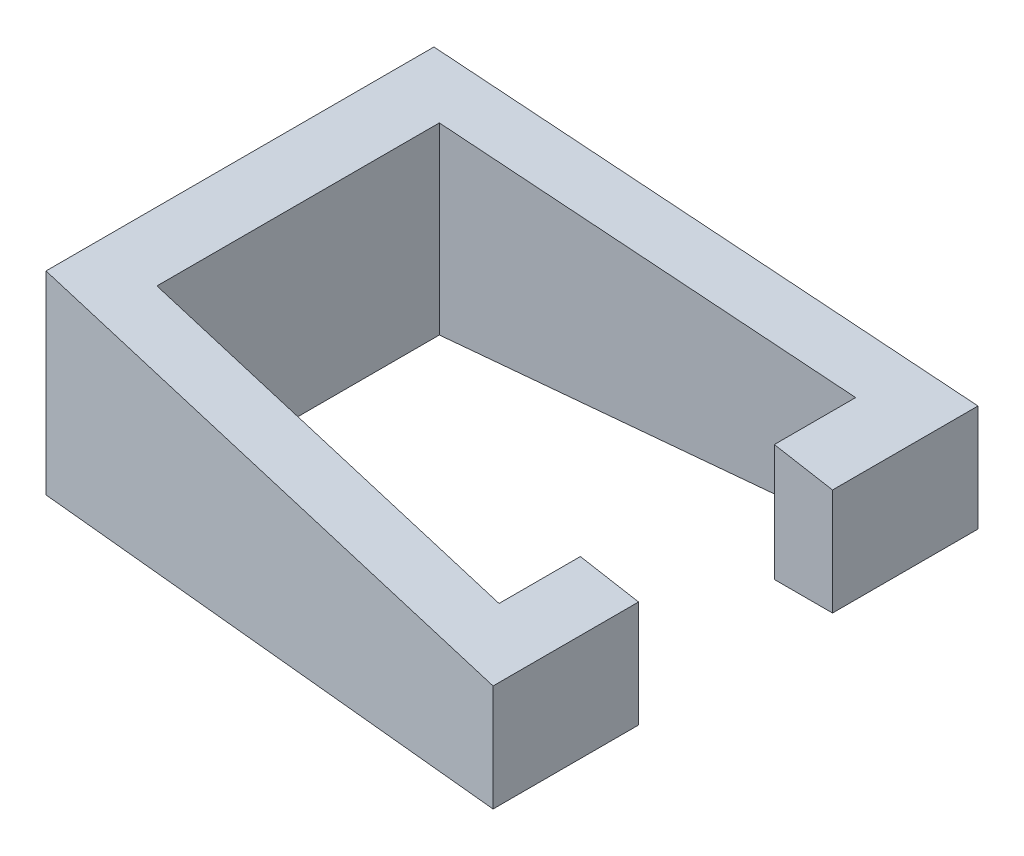
SolidWorks part; units mm, degrees
ref_plane "Front Plane" through (0, 0, 0) normal (0, 0, 1) x (1, 0, 0)
ref_plane "Top Plane" through (0, 0, 0) normal (0, 1, 0) x (1, 0, 0)
ref_plane "Right Plane" through (0, 0, 0) normal (1, 0, 0) x (0, 0, -1)
sketch "Sketch1" plane through (0, 0, 0) normal (0, 1, 0) x (1, 0, 0)
  line L0 (-16.3926, 0) -> (30.937, 0) construction
  line L1 (-10.7677, 0) -> (-10.7677, -10)
  line L2 (-10.7677, -10) -> (14.7803, -12.5)
  line L3 (14.7803, -12.5) -> (14.7803, -5)
  line L4 (-7.7677, 0) -> (-7.7677, -7.2792)
  line L5 (-7.7677, -7.2792) -> (11.7803, -9.1921)
  line L6 (11.7803, -9.1921) -> (11.7803, -5)
  line L8 (14.7803, -5) -> (11.7803, -5)
  line L9 (14.7803, 5) -> (11.7803, 5)
  line L10 (11.7803, 9.1921) -> (11.7803, 5)
  line L11 (-7.7677, 7.2792) -> (11.7803, 9.1921)
  line L12 (-7.7677, 0) -> (-7.7677, 7.2792)
  line L13 (14.7803, 12.5) -> (14.7803, 5)
  line L14 (-10.7677, 10) -> (14.7803, 12.5)
  line L15 (-10.7677, 0) -> (-10.7677, 10)
  dimension "D1" = 3
  dimension "D2" = 20
  dimension "D3" = 25
  dimension "D4" = 25.67
  dimension "D5" = 10
extrude "Boss-Extrude1" add sketch "Sketch1" along normal blind 15
sketch "Sketch2" plane through (0, 0, 0) normal (0, 0, 1) x (1, 0, 0)
  line L0 (14.7803, 15) -> (14.7803, 5.4952)
  line L1 (14.7803, 15) -> (14.7803, 0) construction
  line L2 (14.7803, 5.4952) -> (-10.7677, 10)
  line L3 (-10.7677, 15) -> (-10.7677, 0) construction
  line L4 (-10.7677, 10) -> (-10.7677, 15)
  line L5 (-10.7677, 15) -> (14.7803, 15)
  dimension "D1" = 5
  dimension "D2" = 10
extrude "Cut-Extrude1" cut sketch "Sketch2" against normal through all both and the other way through all
